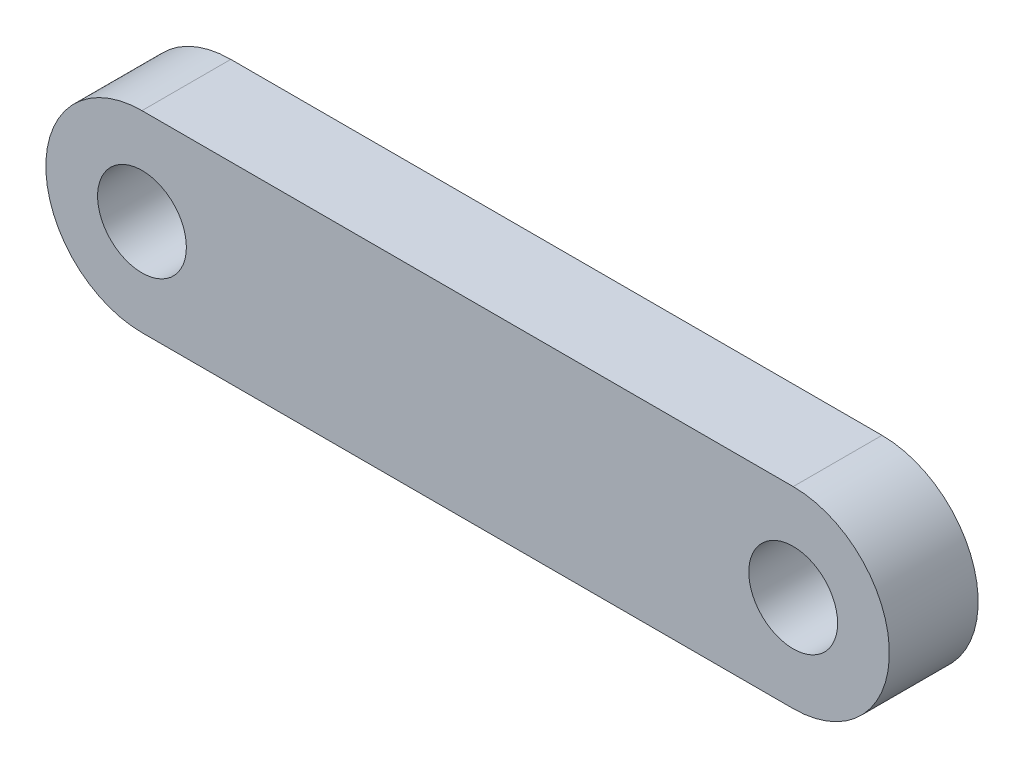
SolidWorks part; units mm, degrees
ref_plane "前基準面" through (0, 0, 0) normal (0, 0, 1) x (1, 0, 0)
ref_plane "上基準面" through (0, 0, 0) normal (0, 1, 0) x (1, 0, 0)
ref_plane "右基準面" through (0, 0, 0) normal (1, 0, 0) x (0, 0, -1)
sketch "草圖1" plane through (0, 0, 0) normal (0, 0, 1) x (1, 0, 0)
  line L0 (221.2993, 136.9846) -> (199.2993, 136.9835)
  line L1 (221.2993, 130.488) -> (199.2993, 130.488)
  arc A0 (221.2993, 130.488) -> (221.2993, 136.9846) centre (221.2993, 133.7363) ccw construction
  arc A1 (199.2993, 136.9835) -> (199.2993, 130.488) centre (199.2993, 133.7357) ccw construction
  circle A2 centre (199.2993, 133.7357) radius 1.5 construction
  circle A3 centre (221.2993, 133.7357) radius 1.5 construction
  arc A4 (221.2993, 130.488) -> (221.2993, 136.9846) centre (221.2993, 133.7363) ccw
  arc A5 (199.2993, 136.9835) -> (199.2993, 130.488) centre (199.2993, 133.7357) ccw
  circle A6 centre (199.2993, 133.7357) radius 1.5
  circle A7 centre (221.2993, 133.7357) radius 1.5
extrude "填料-伸長1" add sketch "草圖1" along normal blind 3
